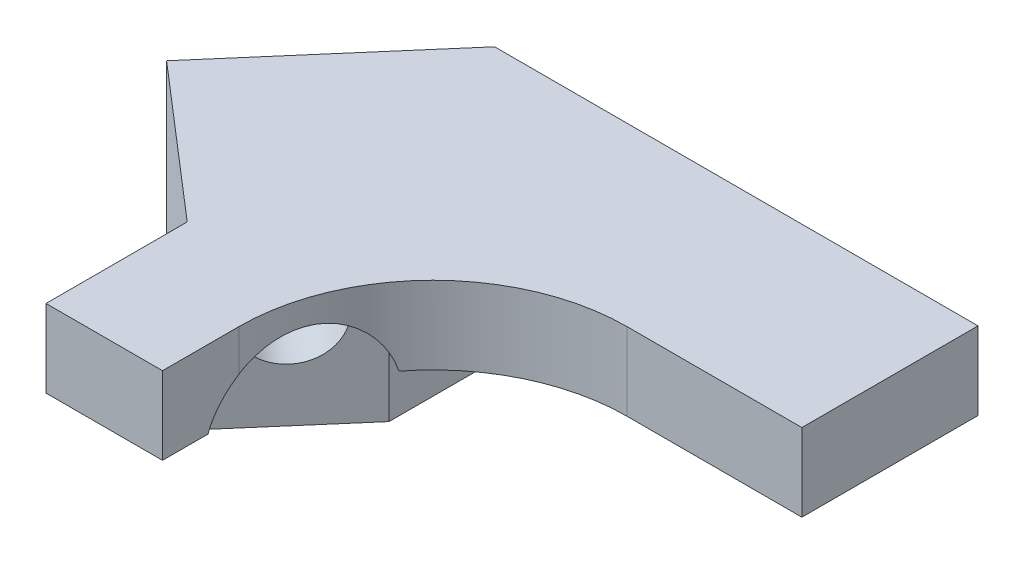
SolidWorks part; units mm, degrees
ref_plane "Front Plane" through (0, 0, 0) normal (0, 0, 1) x (1, 0, 0)
ref_plane "Top Plane" through (0, 0, 0) normal (0, 1, 0) x (1, 0, 0)
ref_plane "Right Plane" through (0, 0, 0) normal (1, 0, 0) x (0, 0, -1)
sketch "Sketch1" plane through (0, 0, 0) normal (0, 1, 0) x (1, 0, 0)
  line L0 (0, 95) -> (-30, 95) construction
  line L1 (0, 130) -> (-150, 130) construction
  line L2 (0, 130) -> (0, -130) construction
  line L3 (0, -130) -> (-150, -130) construction
  line L5 (-30, -80) -> (-30, -85) construction
  line L7 (-30, -10) -> (-169.5228, -130.3307) construction
  line L9 (-169.5228, 130.3307) -> (-153.1953, 149.2624) construction
  line L10 (-153.1953, 149.2624) -> (-30, 80) construction
  line L11 (-150, 130) -> (-161.359, 139.7965) construction
  line L12 (-169.5228, 130.3307) -> (-30, 10) construction
  line L13 (-169.5228, -130.3307) -> (-153.1953, -149.2624) construction
  line L14 (-153.1953, -149.2624) -> (-30, -80) construction
  line L15 (-150, -130) -> (-161.359, -139.7965) construction
  line L16 (-30, 95) -> (-30, 0) construction
  line L17 (-30, 0) -> (-30, -80) construction
  line L18 (-162.9918, 137.9034) -> (-30, 23.2053) construction
  line L19 (-159.8584, 141.5365) -> (-30, 68.5279) construction
  line L20 (-30, 80) -> (-34.9007, 71.2832) construction
  line L29 (-30, 23.2053) -> (-36.531, 15.6326) construction
  line L30 (-150, 130) -> (-138.641, 120.2035) construction
  line L31 (-138.641, 120.2035) -> (-146.8047, 110.7376) construction
  line L32 (-138.641, 120.2035) -> (-133.1788, 126.5368) construction
  line L33 (-133.1788, 126.5368) -> (-128.2781, 135.2536) construction
  line L34 (-30, -85) -> (0, -85) construction
  point P4 (0, 0)
  dimension "D2" = 150
  dimension "D3" = 95
  dimension "D4" = 70
  dimension "D5" = 30
  dimension "D6" = 10
  dimension "D7" = 25
  dimension "D8" = 5
  dimension "D9" = 15
  dimension "D10" = 70
  dimension "D11" = 145.6202
  dimension "D12" = 15
  dimension "D13" = 10
  dimension "D14" = 30
  dimension "D15" = 30
  dimension "D16" = 10
  dimension "D17" = 10
  dimension "D28" = 112.7455
  dimension "D29" = 120
sketch "Sketch2" plane through (0, 0, 0) normal (0, 1, 0) x (1, 0, 0)
  line L0 (-32.7182, 13.929) -> (-24.895, 23)
  line L1 (-24.895, 23) -> (0, 23)
  line L2 (0, 130) -> (0, -130) construction
  line L3 (0, 23) -> (0, 13.929)
  line L4 (0, 13.929) -> (-19, 13.929)
  line L5 (-19, 13.929) -> (-19, 0)
  line L6 (-19, 0) -> (-25, 0)
  line L7 (-25, 0) -> (-25, 7.2724)
  line L8 (-25, 7.2724) -> (-32.7182, 13.929)
  line L9 (-30, 23.2053) -> (-36.531, 15.6326) construction
  line L10 (-30, 95) -> (-30, 0) construction
  dimension "D1" = 4
  dimension "D2" = 1.2
  dimension "D3" = 5
  dimension "D4" = 23
  dimension "D5" = 6
extrude "Boss-Extrude1" add sketch "Sketch2" against normal blind 4
sketch "Sketch3" plane through (0, -4, 0) normal (0, 1, 0) x (-1, 0, 0)
  line L0 (25.7573, -7.9255) -> (32.7182, -13.929)
  line L2 (32.7182, -13.929) -> (24.895, -23)
  line L3 (24.895, -23) -> (20.895, -23)
  line L5 (20.895, -13.5633) -> (25.7573, -7.9255)
  line L6 (20.895, -13.5633) -> (20.895, -23)
  line L8 (0, -23) -> (24.895, -23) construction
  dimension "D1" = 1
  dimension "D2" = 4
extrude "Boss-Extrude2" add sketch "Sketch3" against normal blind 6
sketch "Sketch4" plane through (-25.6514, 0, -22.1229) normal (-0.7573, 0, -0.6531) x (-0.6531, 0, 0.7573)
  circle A0 centre (7.0204, -5) radius 2.25
  dimension "D2" = 4.5
  dimension "D3" = 5
  dimension "D1" = 5
extrude "Cut-Extrude1" cut sketch "Sketch4" against normal through all
ref_plane "Plane1" through (-17.9332, 0, -15.4664) normal (0.7573, 0, 0.6531) x (0.6531, 0, -0.7573)
sketch "Sketch5" plane through (-18.6904, 0, -16.1195) normal (0.7573, 0, 0.6531) x (0.6531, 0, -0.7573)
  circle A0 centre (-7.0204, -5) radius 3.75
  dimension "D1" = 7.5
extrude "Cut-Extrude2" cut sketch "Sketch5" along normal up to next
fillet "Fillet1" radius 10 1 edges at (-19, -2, -13.929)
fillet "Fillet3" radius 2 1 edges at (-20.895, -4, -18.2817)
